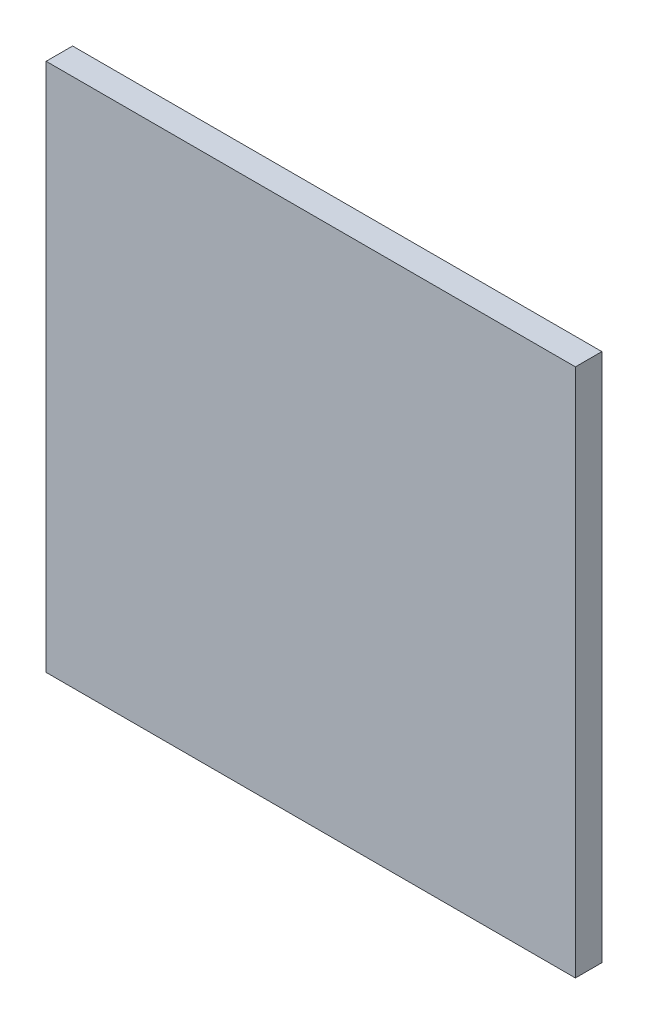
SolidWorks part; units mm, degrees
ref_plane "Front Plane" through (0, 0, 0) normal (0, 0, 1) x (1, 0, 0)
ref_plane "Top Plane" through (0, 0, 0) normal (0, 1, 0) x (1, 0, 0)
ref_plane "Right Plane" through (0, 0, 0) normal (1, 0, 0) x (0, 0, -1)
sketch "Sketch1" plane through (0, 0, 0) normal (0, 0, 1) x (1, 0, 0)
  line L1 (0, 0) -> (10, 0)
  line L2 (0, 0) -> (0, -10)
  line L3 (0, -10) -> (10, -10)
  line L4 (10, 0) -> (10, -10)
  dimension "D1" = 10
  dimension "D2" = 10
extrude "Boss-Extrude1" add sketch "Sketch1" along normal blind 0.5
